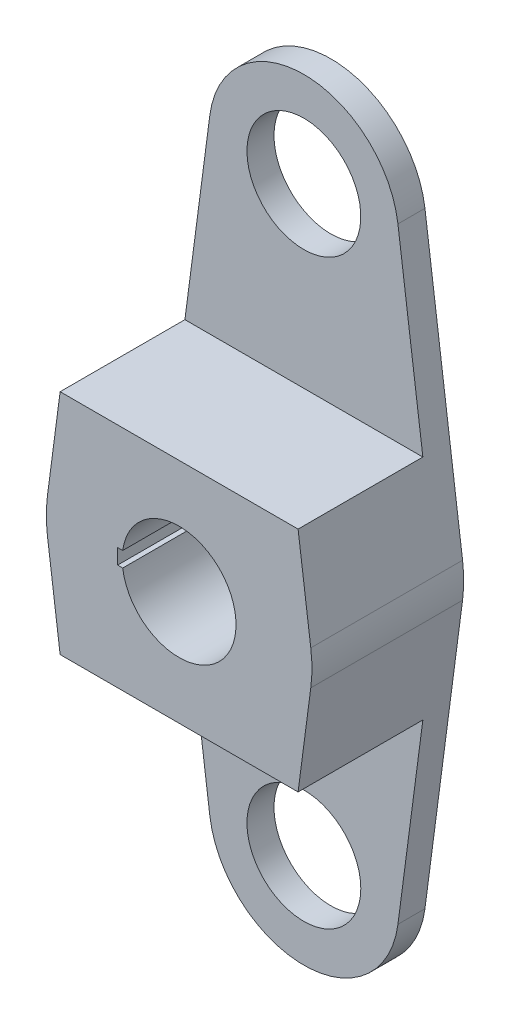
SolidWorks part; units mm, degrees
ref_plane "Front Plane" through (0, 0, 0) normal (0, 0, 1) x (1, 0, 0)
ref_plane "Top Plane" through (0, 0, 0) normal (0, 1, 0) x (1, 0, 0)
ref_plane "Right Plane" through (0, 0, 0) normal (1, 0, 0) x (0, 0, -1)
sketch "Sketch1" plane through (0, 0, 0) normal (0, 0, 1) x (1, 0, 0)
  line L0 (7.8697, 25.3762) -> (11.0176, 1.4495)
  line L1 (11.0176, -1.4495) -> (7.8697, -25.3762)
  line L2 (-7.8697, -25.3762) -> (-11.0176, -1.4495)
  line L3 (-11.0176, 1.4495) -> (-7.8697, 25.3762)
  line L4 (0, -38.2395) -> (0, 38.2395) construction
  circle A0 centre (0, 0) radius 4.7625
  circle A1 centre (0, 24.3408) radius 4.7625
  circle A2 centre (0, -24.3408) radius 4.7625
  circle A3 centre (0, 24.3408) radius 7.9375
  circle A4 centre (0, -24.3408) radius 7.9375
  circle A5 centre (0, 0) radius 11.1125
  point P24 (0, 0)
  dimension "D1" = 9.525
  dimension "D2" = 9.525
  dimension "D3" = 9.525
  dimension "D4" = 24.3408
  dimension "D5" = 24.3408
  dimension "D6" = 3.175
  dimension "D7" = 6.35
extrude "Boss-Extrude1" add sketch "Sketch1" along normal blind 3.175 contours L4 A5 L0 A3 | L4 A3 A1 | A3 L4 A1 | A5 L4 A3 L3 | A5 L4 A0 | L4 A5 A0 | L4 A4 L1 A5 | A4 L4 A5 L2 | A4 L4 A2 | L4 A4 A2
sketch "Sketch2" plane through (0, 0, 0) normal (0, 0, -1) x (-1, 0, 0)
  line L0 (-9.9551, 9.525) -> (9.9551, 9.525)
  line L1 (-7.8697, 25.3762) -> (-11.0176, 1.4495) construction
  line L2 (11.0176, 1.4495) -> (7.8697, 25.3762) construction
  line L3 (-9.9551, -9.525) -> (9.9551, -9.525)
  line L4 (-11.0176, -1.4495) -> (-7.8697, -25.3762) construction
  line L5 (7.8697, -25.3762) -> (11.0176, -1.4495) construction
  line L6 (9.9551, 9.525) -> (11.0176, 1.4495)
  line L7 (11.0176, -1.4495) -> (9.9551, -9.525)
  line L8 (-9.9551, -9.525) -> (-11.0176, -1.4495)
  line L9 (-11.0176, 1.4495) -> (-9.9551, 9.525)
  arc A0 (-11.0176, -1.4495) -> (-11.0176, 1.4495) centre (0, 0) cw
  arc A1 (11.0176, 1.4495) -> (11.0176, -1.4495) centre (0, 0) cw
  circle A2 centre (0, 0) radius 3.175
  dimension "D3" = 6.35
  dimension "D1" = 19.05
  dimension "D2" = 9.525
extrude "Boss-Extrude2" add sketch "Sketch2" along normal blind 3.175
sketch "Sketch3" plane through (0, 0, 3.175) normal (0, 0, 1) x (1, 0, 0)
  line L0 (-9.9551, 9.525) -> (9.9551, 9.525)
  line L1 (-11.0176, 1.4495) -> (-7.8697, 25.3762) construction
  line L2 (7.8697, 25.3762) -> (11.0176, 1.4495) construction
  line L3 (-9.9551, -9.525) -> (9.9551, -9.525)
  line L4 (-7.8697, -25.3762) -> (-11.0176, -1.4495) construction
  line L5 (11.0176, -1.4495) -> (7.8697, -25.3762) construction
  line L6 (-9.9551, 9.525) -> (-11.0176, 1.4495)
  line L7 (-9.9551, -9.525) -> (-11.0176, -1.4495)
  line L8 (9.9551, -9.525) -> (11.0176, -1.4495)
  line L9 (9.9551, 9.525) -> (11.0176, 1.4495)
  arc A0 (-11.0176, 1.4495) -> (-11.0176, -1.4495) centre (0, 0) ccw
  arc A1 (11.0176, 1.4495) -> (11.0176, -1.4495) centre (0, 0) cw
  circle A2 centre (0, 0) radius 4.7625
  dimension "D1" = 19.05
  dimension "D2" = 9.525
extrude "Boss-Extrude3" add sketch "Sketch3" along normal blind 6.35
sketch "Sketch4" plane through (0, 0, 0) normal (0, 0, -1) x (-1, 0, 0)
  line L0 (0, 0) -> (11.1125, 0) construction
  line L1 (9.9551, 9.525) -> (-9.9551, 9.525)
  line L2 (-9.9551, 9.525) -> (-7.8697, 25.3762)
  line L3 (9.9551, 9.525) -> (7.8697, 25.3762)
  line L4 (-9.9551, -9.525) -> (-7.8697, -25.3762)
  line L5 (9.9551, -9.525) -> (-9.9551, -9.525)
  line L6 (9.9551, -9.525) -> (7.8697, -25.3762)
  circle A0 centre (0, 24.3408) radius 4.7625
  arc A1 (11.0176, -1.4495) -> (11.0176, 1.4495) centre (0, 0) ccw construction
  arc A2 (-7.8697, 25.3762) -> (7.8697, 25.3762) centre (0, 24.3408) cw
  circle A3 centre (0, -24.3408) radius 4.7625
  arc A4 (-7.8697, -25.3762) -> (7.8697, -25.3762) centre (0, -24.3408) ccw
  dimension "D1" = 9.525
extrude "Boss-Extrude4" add sketch "Sketch4" along normal up to surface (3.175 mm away) up to face at (0, 0, -3.175)
sketch "Sketch5" plane through (0, 0, 3.175) normal (0, 0, 1) x (1, 0, 0)
  line L0 (-7.8697, -25.3762) -> (-9.9551, -9.525)
  line L1 (-9.9551, -9.525) -> (9.9551, -9.525)
  line L2 (9.9551, -9.525) -> (7.8697, -25.3762)
  line L3 (0, 0) -> (11.1125, 0) construction
  line L4 (-7.8697, 25.3762) -> (-9.9551, 9.525)
  line L5 (-9.9551, 9.525) -> (9.9551, 9.525)
  line L6 (9.9551, 9.525) -> (7.8697, 25.3762)
  arc A0 (-7.8697, -25.3762) -> (7.8697, -25.3762) centre (0, -24.3408) ccw
  arc A1 (11.0176, -1.4495) -> (11.0176, 1.4495) centre (0, 0) ccw construction
  arc A2 (-7.8697, 25.3762) -> (7.8697, 25.3762) centre (0, 24.3408) cw
extrude "Cut-Extrude1" cut sketch "Sketch5" against normal blind 4.0894
sketch "Sketch6" plane through (0, 0, 9.525) normal (0, 0, 1) x (1, 0, 0)
  line L0 (0, 0) -> (-4.7625, 0) construction
  line L2 (-5.1435, -0.635) -> (-4.3815, -0.635)
  line L3 (-5.1435, -0.635) -> (-5.1435, 0.635)
  line L4 (-5.1435, 0.635) -> (-4.3815, 0.635)
  line L5 (-4.3815, -0.635) -> (-4.3815, 0.635)
  line L6 (-5.1435, -0.635) -> (-4.3815, 0.635) construction
  line L7 (-5.1435, 0.635) -> (-4.3815, -0.635) construction
  circle A0 centre (0, 0) radius 4.7625 construction
  dimension "D1" = 0.762
  dimension "D2" = 1.27
extrude "Cut-Extrude2" cut sketch "Sketch6" against normal up to surface (9.525 mm away) up to face at (4.7625, 0, 0)
